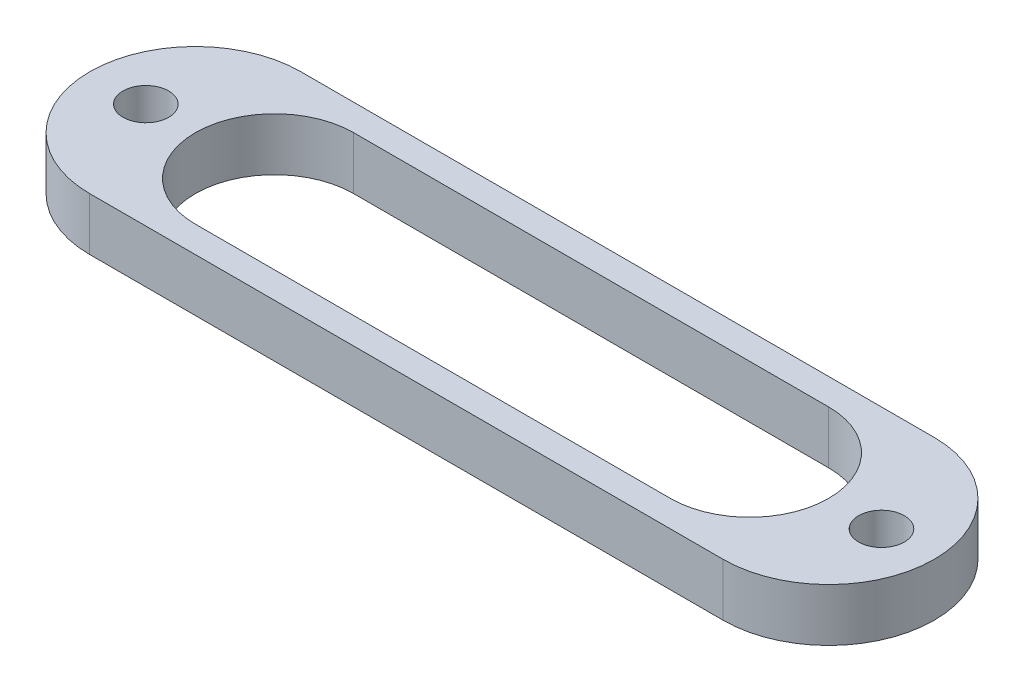
SolidWorks part; units mm, degrees
ref_plane "Front Plane" through (0, 0, 0) normal (0, 0, 1) x (1, 0, 0)
ref_plane "Top Plane" through (0, 0, 0) normal (0, 1, 0) x (1, 0, 0)
ref_plane "Right Plane" through (0, 0, 0) normal (1, 0, 0) x (0, 0, -1)
sketch "Sketch2" plane through (0, 0, 0) normal (0, 1, 0) x (1, 0, 0)
  line L0 (0, 0) -> (76.2, 0) construction
  line L1 (0, 12.7) -> (76.2, 12.7)
  line L2 (0, -12.7) -> (76.2, -12.7)
  line L3 (9.525, 0) -> (66.675, 0) construction
  line L4 (9.525, 9.525) -> (66.675, 9.525)
  line L5 (9.525, -9.525) -> (66.675, -9.525)
  arc A0 (0, 12.7) -> (0, -12.7) centre (0, 0) ccw
  arc A1 (76.2, -12.7) -> (76.2, 12.7) centre (76.2, 0) ccw
  arc A2 (9.525, 9.525) -> (9.525, -9.525) centre (9.525, 0) ccw
  arc A3 (66.675, -9.525) -> (66.675, 9.525) centre (66.675, 0) ccw
  point P3 (38.1, 0)
  point P10 (38.1, 0)
  point P15 (0, 0)
  dimension "D2" = 12.7
  dimension "D4" = 9.525
  dimension "D1" = 76.2
  dimension "D3" = 57.15
extrude "Boss-Extrude1" add sketch "Sketch2" along normal blind 6.35
sketch "Sketch3" plane through (0, 6.35, 0) normal (0, 1, 0) x (1, 0, 0)
  arc A0 (0, 12.7) -> (0, -12.7) centre (0, 0) ccw construction
  arc A1 (76.2, -12.7) -> (76.2, 12.7) centre (76.2, 0) ccw construction
  point P0 (-5.95, 0)
  point P1 (82.55, 0)
  point P8 (0, 0)
  dimension "D1" = 5.95
  dimension "D2" = 6.35
hole_wizard "M5 Clearance Hole1" positions "Sketch4" profile "Sketch5" hole size "M5" standard "ANSI Metric" end condition through all
sketch "Sketch4" plane through (0, 6.35, 0) normal (0, 1, 0) x (1, 0, 0)
  point P0 (-5.95, 0)
  point P3 (82.55, 0)
sketch "Sketch5" plane through (-5.95, 6.35, 0) normal (1, 0, 0) x (0, 0, 1)
  line L0 (0, 0) -> (0, 6.35)
  line L1 (0, 6.35) -> (2.75, 6.35)
  line L2 (2.75, 6.35) -> (2.75, 0)
  line L5 (2.75, 0) -> (0, 0)
  line L11 (0, -6.35) -> (0, 107.95) construction
  dimension "Thru Hole Dia." = 5.5
  dimension "Thru Hole Depth" = 6.35
